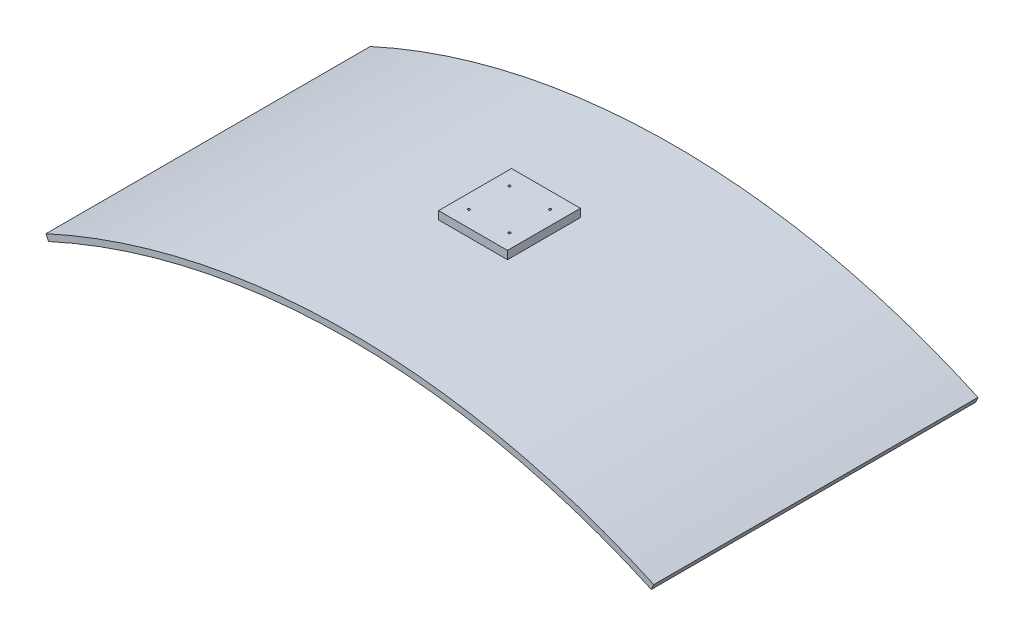
SolidWorks part; units mm, degrees
ref_plane "Plan de face" through (0, 0, 0) normal (0, 0, 1) x (1, 0, 0)
ref_plane "Plan de dessus" through (0, 0, 0) normal (0, 1, 0) x (1, 0, 0)
ref_plane "Plan de droite" through (0, 0, 0) normal (1, 0, 0) x (0, 0, -1)
sketch "Esquisse1" plane through (0, 0, 0) normal (0, 0, 1) x (1, 0, 0)
  arc A0 (0, 0) -> (1500, 0) centre (750, -1636.3068) cw
  dimension "D1" = 1800
  dimension "D2" = 1500
extrude "Extru.-Mince1" add sketch "Esquisse1" along normal blind 800 thin
sketch "Esquisse2" plane through (0, 0, 800) normal (0, 0, 1) x (1, 0, 0)
  line L2 (15.3406, -9.4692) -> (9.0906, 4.1667)
  line L3 (15.3523, -9.4947) -> (14.9356, -8.5856)
  line L5 (1490.9094, 4.1667) -> (1484.6594, -9.4692)
  line L6 (1485.0644, -8.5856) -> (1484.6477, -9.4947)
  arc A1 (1493.75, -13.6359) -> (6.25, -13.6359) centre (750, -1636.3068) ccw construction
  arc A2 (1494.1667, -12.7268) -> (5.8333, -12.7268) centre (750, -1636.3068) ccw
  arc A3 (1485.0644, -8.5856) -> (14.9356, -8.5856) centre (750, -1636.3068) ccw
  arc A4 (1484.6477, -9.4947) -> (15.3523, -9.4947) centre (750, -1636.3068) ccw
  dimension "D1" = 1
  dimension "D2" = 10
  dimension "D3" = 10
extrude "Enlèv. mat.-Extru.1" cut sketch "Esquisse2" against normal blind 780 from offset 10 offset against normal yes
sketch "Esquisse3" plane through (0, 0, 0) normal (0, 1, 0) x (1, 0, 0)
  line L0 (750, 0) -> (750, -800) construction
  line L1 (1500, 0) -> (0, 0) construction
  line L2 (0, -800) -> (1500, -800) construction
  circle A0 centre (750, -190) radius 35
  dimension "D1" = 70
  dimension "D2" = 190
ref_plane "Plane1" through (743.75, 0, 0) normal (1, 0, 0) x (0, 0, -1)
sketch "Sketch2" plane through (743.75, 0, 0) normal (1, 0, 0) x (0, 0, -1)
  line L0 (-400, 163.6932) -> (-400, 203.6932) construction
  line L1 (0, 163.6932) -> (-800, 163.6932) construction
  line L2 (-390, 163.6932) -> (-390, 203.6932)
  line L3 (-410, 163.6932) -> (-410, 203.6932)
  line L4 (-410, 203.6932) -> (-390, 203.6932)
  line L5 (-390, 163.6932) -> (-410, 163.6932)
  dimension "D1" = 40
  dimension "D2" = 10
  dimension "D3" = 10
extrude "Boss-Extrude1" add sketch "Sketch2" along normal mid plane 90 separate body
sketch "Sketch3" plane through (0, 203.6932, 0) normal (0, 1, 0) x (1, 0, 0)
  line L0 (788.75, -390) -> (698.75, -390) construction
  line L1 (658.8298, -310) -> (828.8298, -310)
  line L2 (658.8298, -310) -> (658.8298, -490)
  line L3 (658.8298, -490) -> (828.8298, -490)
  line L4 (828.8298, -310) -> (828.8298, -490)
  line L5 (658.8298, -310) -> (828.8298, -490) construction
  line L6 (658.8298, -490) -> (828.8298, -310) construction
  line L8 (788.75, -410) -> (698.75, -410) construction
  point P0 (743.8298, -400)
  dimension "D1" = 80
  dimension "D2" = 80
  dimension "D3" = 170
extrude "Boss-Extrude2" add sketch "Sketch3" along normal blind 20
sketch "Sketch4" plane through (0, 223.6932, 0) normal (0, 1, 0) x (1, 0, 0)
  circle A0 centre (693.8298, -450) radius 3
  circle A1 centre (793.8298, -450) radius 3
  circle A2 centre (693.8298, -350) radius 3
  circle A3 centre (793.8298, -350) radius 3
  dimension "D1" = 6
extrude "Cut-Extrude1" cut sketch "Sketch4" against normal up to vertex (20 mm away)
